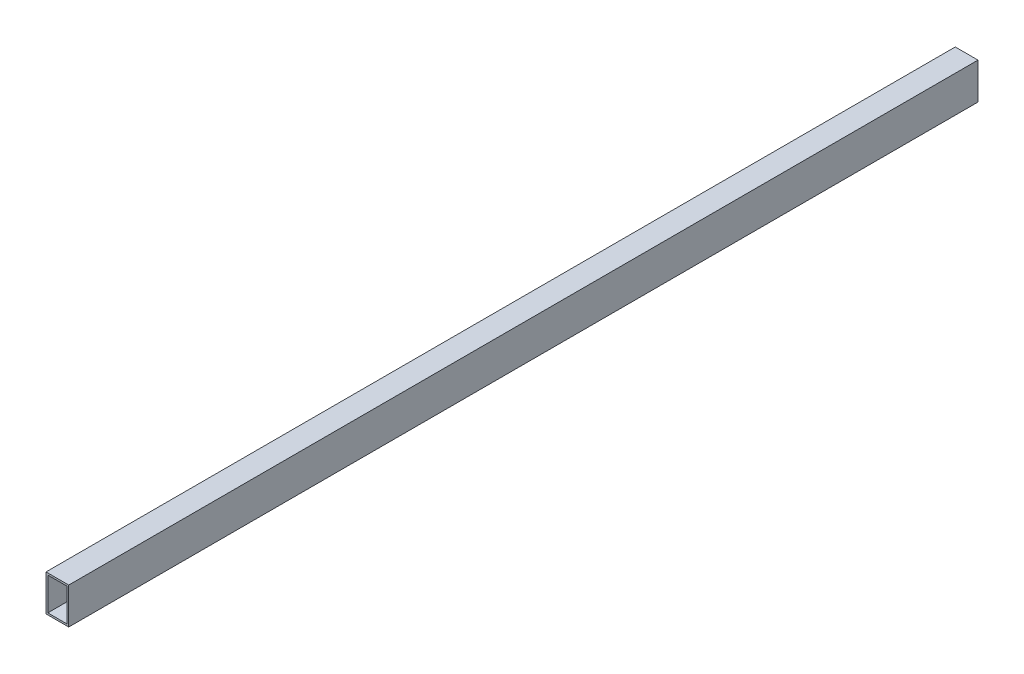
SolidWorks part; units mm, degrees
ref_plane "Front Plane" through (0, 0, 0) normal (0, 0, 1) x (1, 0, 0)
ref_plane "Top Plane" through (0, 0, 0) normal (0, 1, 0) x (1, 0, 0)
ref_plane "Right Plane" through (0, 0, 0) normal (1, 0, 0) x (0, 0, -1)
sketch "Sketch1" plane through (0, 0, 0) normal (0, 0, 1) x (1, 0, 0)
  line L1 (-25, 40) -> (25, 40)
  line L2 (-25, 40) -> (-25, -40)
  line L3 (-25, -40) -> (25, -40)
  line L4 (25, 40) -> (25, -40)
  point P0 (0, 0)
  point P7 (0, 0)
  dimension "D1" = 80
  dimension "D2" = 50
extrude "Boss-Extrude1" add sketch "Sketch1" along normal blind 2000 contours L1 L4 L3 L2
sketch "Sketch2" plane through (0, 0, 0) normal (0, 0, -1) x (-1, 0, 0)
  line L1 (-21, 36) -> (21, 36)
  line L2 (-21, 36) -> (-21, -36)
  line L3 (-21, -36) -> (21, -36)
  line L4 (21, 36) -> (21, -36)
  line L5 (-21, 36) -> (21, -36) construction
  line L6 (-21, -36) -> (21, 36) construction
  point P0 (0, 0)
  dimension "D1" = 42
  dimension "D2" = 72
extrude "Cut-Extrude1" cut sketch "Sketch2" against normal blind 2000
